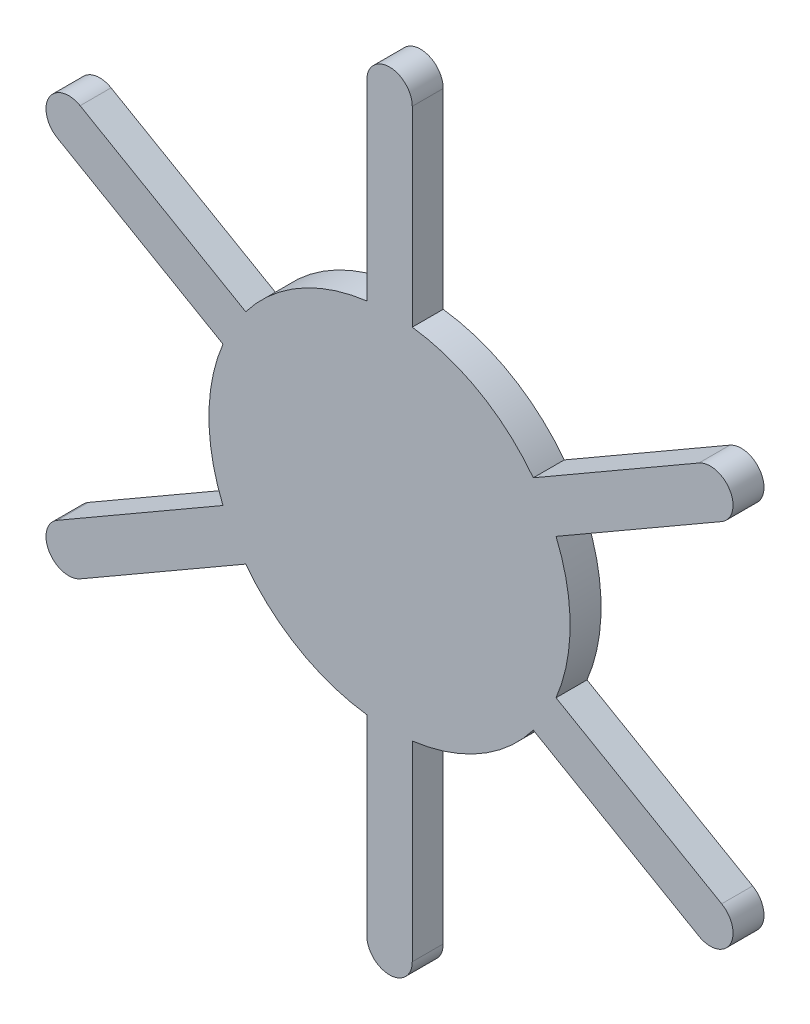
SolidWorks part; units mm, degrees
ref_plane "Front Plane" through (0, 0, 0) normal (0, 0, 1) x (1, 0, 0)
ref_plane "Top Plane" through (0, 0, 0) normal (0, 1, 0) x (1, 0, 0)
ref_plane "Right Plane" through (0, 0, 0) normal (1, 0, 0) x (0, 0, -1)
other "Center of Mass"
sketch "Sketch1" plane through (0, 0, 0) normal (0, 0, 1) x (1, 0, 0)
  line L0 (-299.8147, 198.5404) -> (-139.3315, 105.8854)
  line L2 (-22.0337, -358.9173) -> (-22.0337, -173.6074)
  line L4 (22.0337, -358.9173) -> (22.0337, -173.6074)
  line L6 (22.0337, 173.6074) -> (22.0337, 358.9173)
  line L7 (-321.8484, 160.3769) -> (-161.3652, 67.7219)
  line L8 (321.8484, 160.3769) -> (161.3652, 67.7219)
  line L9 (299.8147, 198.5404) -> (139.3315, 105.8854)
  line L10 (-22.0337, 173.6074) -> (-22.0337, 358.9173)
  line L13 (-161.3652, -67.7219) -> (-321.8484, -160.3769)
  line L14 (-139.3315, -105.8854) -> (-299.8147, -198.5404)
  line L17 (139.3315, -105.8854) -> (299.8147, -198.5404)
  line L18 (161.3652, -67.7219) -> (321.8484, -160.3769)
  arc A0 (-22.0337, 173.6074) -> (-139.3315, 105.8854) centre (0, 0) ccw
  arc A1 (22.0337, 358.9173) -> (-22.0337, 358.9173) centre (0, 358.9173) ccw
  arc A2 (22.0337, -358.9173) -> (-22.0337, -358.9173) centre (0, -358.9173) cw
  arc A3 (299.8147, -198.5404) -> (321.8484, -160.3769) centre (310.8315, -179.4587) ccw
  arc A4 (-321.8484, 160.3769) -> (-299.8147, 198.5404) centre (-310.8315, 179.4587) cw
  arc A5 (-321.8484, -160.3769) -> (-299.8147, -198.5404) centre (-310.8315, -179.4587) ccw
  arc A6 (299.8147, 198.5404) -> (321.8484, 160.3769) centre (310.8315, 179.4587) cw
  arc A7 (-161.3652, 67.7219) -> (-161.3652, -67.7219) centre (0, 0) ccw
  arc A8 (-139.3315, -105.8854) -> (-22.0337, -173.6074) centre (0, 0) ccw
  arc A9 (22.0337, -173.6074) -> (139.3315, -105.8854) centre (0, 0) ccw
  arc A10 (161.3652, -67.7219) -> (161.3652, 67.7219) centre (0, 0) ccw
  arc A11 (139.3315, 105.8854) -> (22.0337, 173.6074) centre (0, 0) ccw
  point P23 (0, 0)
  dimension "D1" = 350
  dimension "D2" = 3
extrude "Boss-Extrude1" add sketch "Sketch1" along normal mid plane 30
